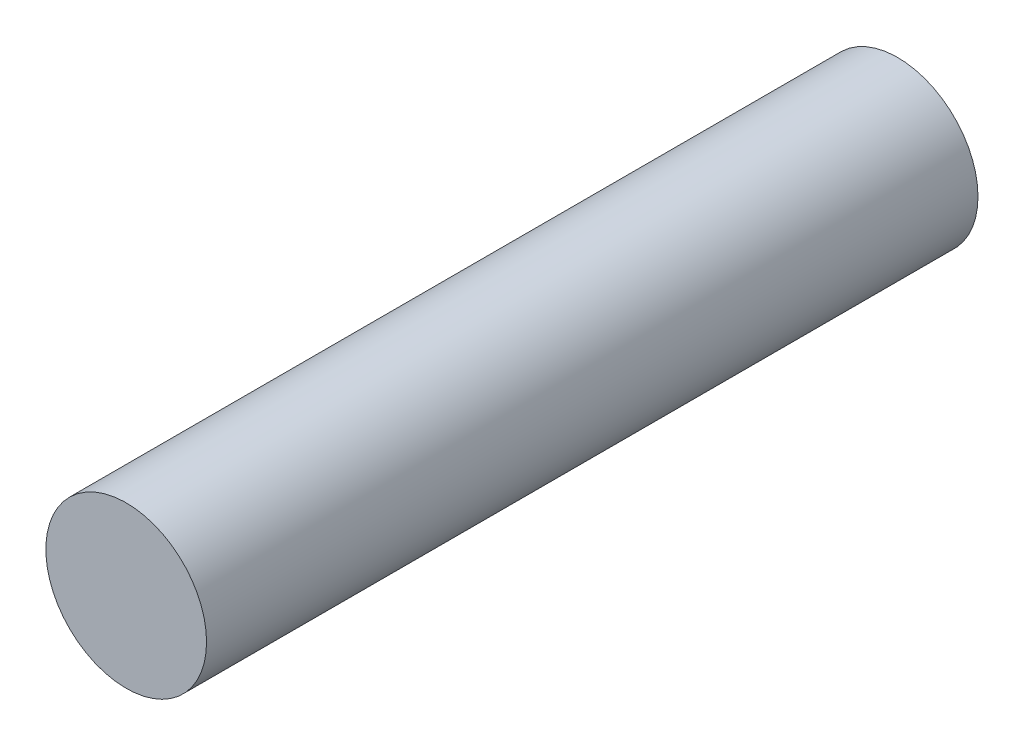
SolidWorks part; units mm, degrees
ref_plane "Front Plane" through (0, 0, 0) normal (0, 0, 1) x (1, 0, 0)
ref_plane "Top Plane" through (0, 0, 0) normal (0, 1, 0) x (1, 0, 0)
ref_plane "Right Plane" through (0, 0, 0) normal (1, 0, 0) x (0, 0, -1)
sketch "Sketch2" plane through (0, 0, 0) normal (0, 0, 1) x (1, 0, 0)
  circle A0 centre (0, 0) radius 2.5
  dimension "D1" = 5
extrude "Boss-Extrude1" add sketch "Sketch2" along normal blind 24
